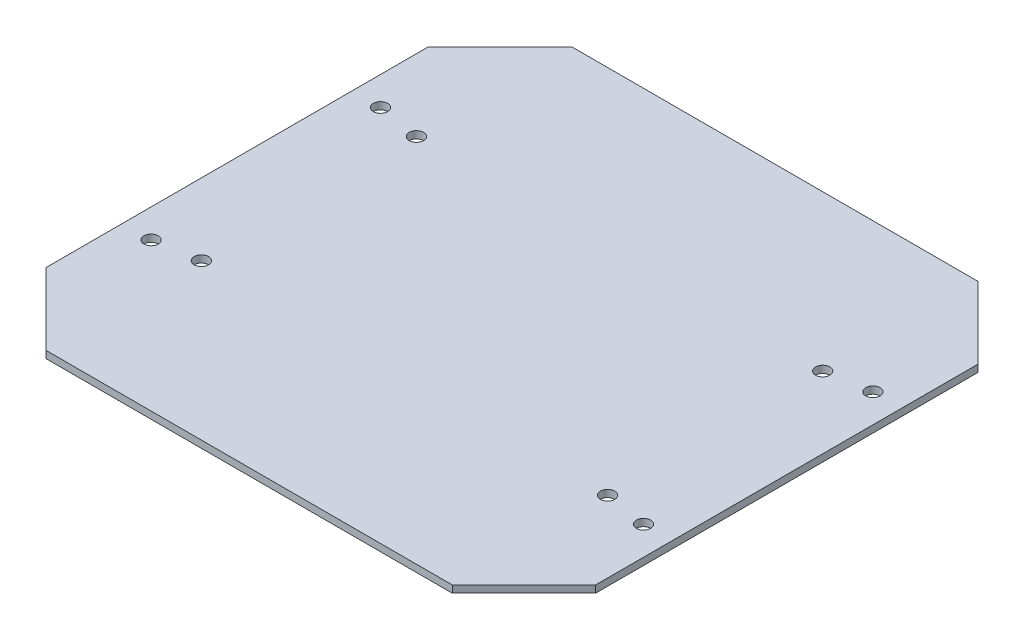
SolidWorks part; units mm, degrees
ref_plane "Front Plane" through (0, 0, 0) normal (0, 0, 1) x (1, 0, 0)
ref_plane "Top Plane" through (0, 0, 0) normal (0, 1, 0) x (1, 0, 0)
ref_plane "Right Plane" through (0, 0, 0) normal (1, 0, 0) x (0, 0, -1)
sketch "Sketch1" plane through (0, 0, 0) normal (0, 1, 0) x (1, 0, 0)
  line L1 (-57.5, -55) -> (57.5, -55)
  line L2 (-57.5, -55) -> (-57.5, 55)
  line L3 (-57.5, 55) -> (57.5, 55)
  line L4 (57.5, -55) -> (57.5, 55)
  line L5 (-57.5, -55) -> (57.5, 55) construction
  line L6 (-57.5, 55) -> (57.5, -55) construction
  point P0 (0, 0)
  dimension "D1" = 115
  dimension "D2" = 110
extrude "Boss-Extrude1" add sketch "Sketch1" along normal blind 1.5
chamfer "Chamfer1" distance 15 angle 45 4 edges at (-57.5, 0.75, 55) (57.5, 0.75, 55) (57.5, 0.75, -55) (-57.5, 0.75, -55)
sketch "Sketch3" plane through (0, 1.5, 0) normal (0, 1, 0) x (1, 0, 0)
  line L1 (-51.515, -24) -> (51.515, -24) construction
  line L2 (-51.515, -24) -> (-51.515, 24) construction
  line L3 (-51.515, 24) -> (51.515, 24) construction
  line L4 (51.515, -24) -> (51.515, 24) construction
  line L5 (-51.515, -24) -> (51.515, 24) construction
  line L6 (-51.515, 24) -> (51.515, -24) construction
  circle A0 centre (-51.515, 24) radius 1.5
  circle A1 centre (51.515, 24) radius 1.5
  circle A2 centre (51.515, -24) radius 1.5
  circle A3 centre (-51.515, -24) radius 1.5
  point P0 (0, 0)
  dimension "D3" = 3
  dimension "D1" = 48
  dimension "D2" = 103.03
extrude "Cut-Extrude1" cut sketch "Sketch3" against normal up to surface (1.5 mm away) up to face at (0, 0, 0)
sketch "Sketch4" plane through (0, 1.5, 0) normal (0, 1, 0) x (1, 0, 0)
  line L1 (-42.5, -22.5) -> (42.5, -22.5) construction
  line L2 (-42.5, -22.5) -> (-42.5, 22.5) construction
  line L3 (-42.5, 22.5) -> (42.5, 22.5) construction
  line L4 (42.5, -22.5) -> (42.5, 22.5) construction
  line L5 (-42.5, -22.5) -> (42.5, 22.5) construction
  line L6 (-42.5, 22.5) -> (42.5, -22.5) construction
  circle A0 centre (-42.5, 22.5) radius 1.5
  circle A1 centre (-42.5, -22.5) radius 1.5
  circle A2 centre (42.5, -22.5) radius 1.5
  circle A3 centre (42.5, 22.5) radius 1.5
  point P0 (0, 0)
  dimension "D3" = 3
  dimension "D1" = 85
  dimension "D2" = 45
extrude "Cut-Extrude2" cut sketch "Sketch4" against normal up to surface (1.5 mm away) up to face at (-51.515, 0, 22.5)
